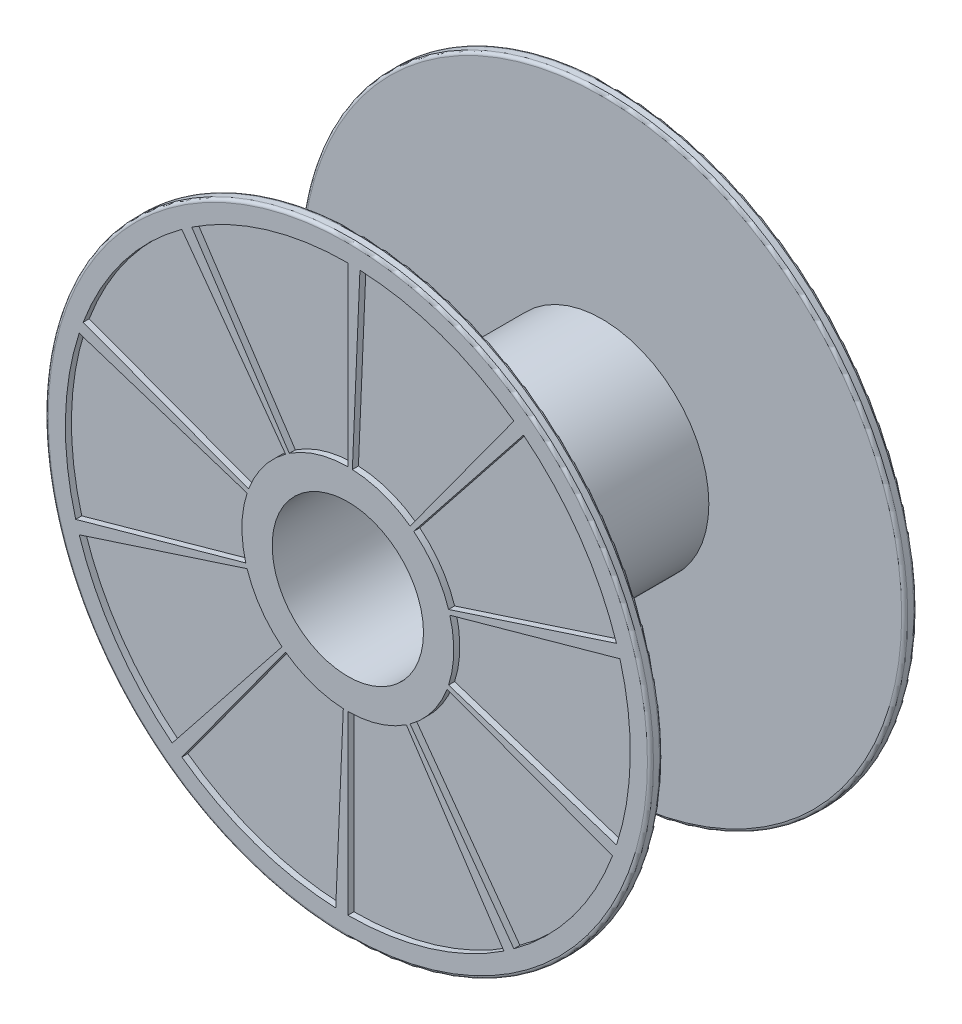
SolidWorks part; units mm, degrees
ref_plane "Přední rovina" through (0, 0, 0) normal (0, 0, 1) x (1, 0, 0)
ref_plane "Horní rovina" through (0, 0, 0) normal (0, 1, 0) x (1, 0, 0)
ref_plane "Pravá rovina" through (0, 0, 0) normal (1, 0, 0) x (0, 0, -1)
sketch "Skica1" plane through (0, 0, 0) normal (0, 0, 1) x (1, 0, 0)
  circle A0 centre (0, 0) radius 100
  circle A1 centre (0, 0) radius 25
  dimension "D1" = 200
  dimension "D2" = 50
extrude "Přidat vysunutím1" add sketch "Skica1" along normal blind 88
ref_plane "Rovina1" through (0, 0, 84) normal (0, 0, 1) x (1, 0, 0)
sketch "Skica2" plane through (0, 0, 84) normal (0, 0, 1) x (1, 0, 0)
  circle A0 centre (0, 0) radius 100
  circle A1 centre (0, 0) radius 35.2882
extrude "Odebrat vysunutím1" cut sketch "Skica2" against normal blind 80
fillet "Zaoblit1" radius 1 4 edges at (100, 0, 0) (100, 0, 4) (100, 0, 84) (100, 0, 88)
sketch "Skica3" plane through (0, 0, 88) normal (0, 0, 1) x (1, 0, 0)
  line L0 (0, 93.3333) -> (0, 35)
  line L1 (4, 93.2476) -> (1.5, 34.9678)
  line L2 (54.86, 75.5083) -> (20.5725, 28.3156)
  line L3 (58.0456, 73.0877) -> (21.7671, 27.4079)
  line L4 (88.7653, 28.8416) -> (33.287, 10.8156)
  line L5 (89.9198, 25.0109) -> (33.7199, 9.3791)
  line L6 (88.7653, -28.8416) -> (33.287, -10.8156)
  line L7 (87.4477, -32.6193) -> (32.7929, -12.2322)
  line L8 (54.86, -75.5083) -> (20.5725, -28.3156)
  line L9 (51.5735, -77.79) -> (19.3401, -29.1713)
  line L10 (0, -93.3333) -> (0, -35)
  line L11 (-4, -93.2476) -> (-1.5, -34.9678)
  line L12 (-54.86, -75.5083) -> (-20.5725, -28.3156)
  line L13 (-58.0456, -73.0877) -> (-21.7671, -27.4079)
  line L14 (-88.7653, -28.8416) -> (-33.287, -10.8156)
  line L15 (-89.9198, -25.0109) -> (-33.7199, -9.3791)
  line L16 (-88.7653, 28.8416) -> (-33.287, 10.8156)
  line L17 (-87.4477, 32.6193) -> (-32.7929, 12.2322)
  line L18 (-54.86, 75.5083) -> (-20.5725, 28.3156)
  line L19 (-51.5735, 77.79) -> (-19.3401, 29.1713)
  circle A0 centre (0, 0) radius 35
  circle A1 centre (0, 0) radius 93.3333
  point P46 (0, 0)
  dimension "D4" = 70
  dimension "D5" = 186.6667
  dimension "D2" = 4
  dimension "D3" = 1.5
  dimension "D1" = 10
extrude "Odebrat vysunutím2" cut sketch "Skica3" against normal blind 2 contours L0 A1 L19 A0 | L18 A1 L17 A0 | L2 A1 L1 A0 | L4 A1 L3 A0 | L6 A1 L5 A0 | L8 A1 L7 A0 | L10 A1 L9 A0 | L12 A1 L11 A0 | L14 A1 L13 A0 | L16 A1 L15 A0
sketch "Skica4" plane through (0, 0, 0) normal (0, 0, -1) x (-1, 0, 0)
  line L0 (0, 35) -> (0, 93.335)
  line L1 (1.5, 34.9678) -> (4, 93.2492)
  line L2 (21.7671, 27.4079) -> (58.0466, 73.0891)
  line L3 (20.5725, 28.3156) -> (54.8609, 75.5096)
  line L4 (33.7199, 9.3791) -> (89.9214, 25.0114)
  line L5 (33.287, 10.8156) -> (88.7669, 28.8421)
  line L6 (32.7929, -12.2322) -> (87.4492, -32.6198)
  line L7 (33.287, -10.8156) -> (88.7669, -28.8421)
  line L8 (19.3401, -29.1712) -> (51.5745, -77.7914)
  line L9 (20.5725, -28.3156) -> (54.8609, -75.5096)
  line L10 (-1.5, -34.9678) -> (-4, -93.2492)
  line L11 (0, -35) -> (0, -93.335)
  line L12 (-21.7671, -27.4079) -> (-58.0466, -73.0891)
  line L13 (-20.5725, -28.3156) -> (-54.8609, -75.5096)
  line L14 (-33.7199, -9.3791) -> (-89.9214, -25.0114)
  line L15 (-33.287, -10.8156) -> (-88.7669, -28.8421)
  line L16 (-32.7929, 12.2322) -> (-87.4492, 32.6198)
  line L17 (-33.287, 10.8156) -> (-88.7669, 28.8421)
  line L18 (-19.3401, 29.1712) -> (-51.5745, 77.7914)
  line L19 (-20.5725, 28.3156) -> (-54.8609, 75.5096)
  circle A0 centre (0, 0) radius 93.335
  circle A1 centre (0, 0) radius 35
  point P46 (0, 0)
  dimension "D1" = 186.67
  dimension "D2" = 70
  dimension "D3" = 4
  dimension "D4" = 1.5
  dimension "D5" = 10
extrude "Odebrat vysunutím3" cut sketch "Skica4" against normal blind 2 contours A1 L0 A0 L18 | A1 L19 A0 L16 | A1 L17 A0 L14 | A1 L15 A0 L12 | A1 L13 A0 L10 | A1 L11 A0 L8 | A1 L9 A0 L6 | A1 L7 A0 L4 | A1 L5 A0 L2 | A1 L3 A0 L1
